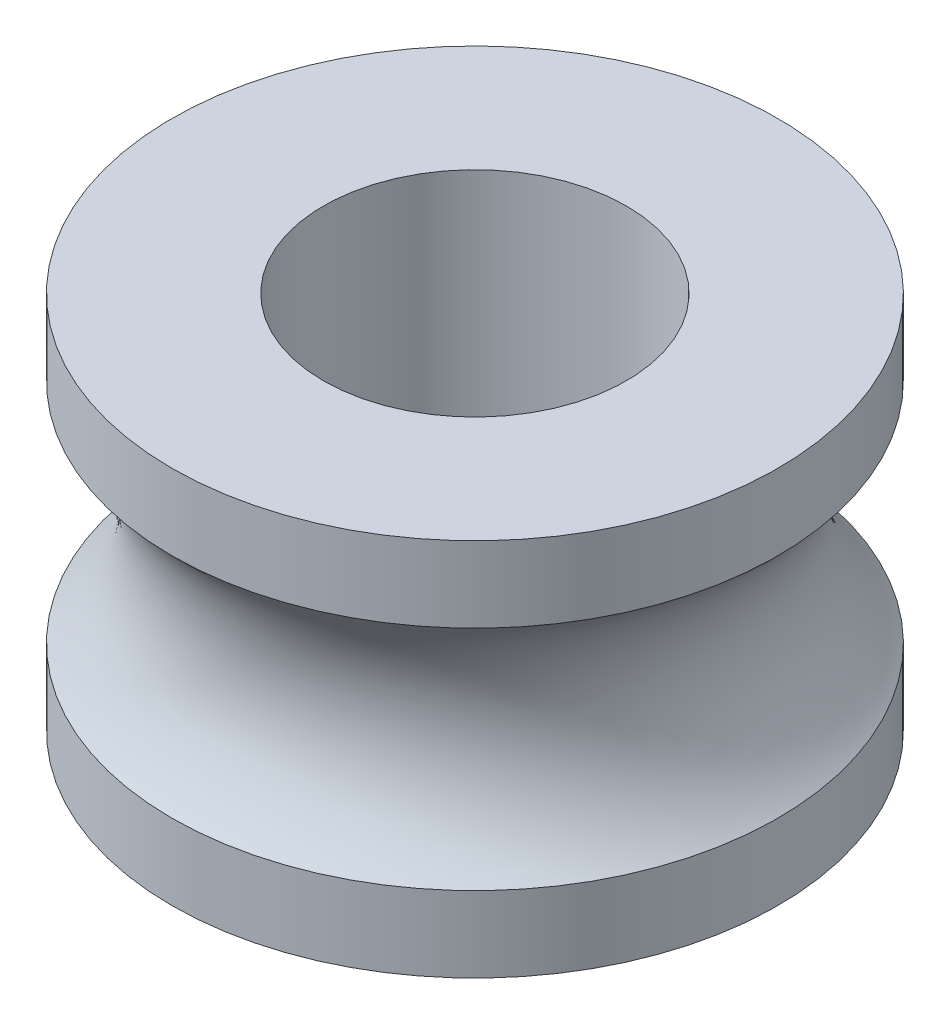
SolidWorks part; units mm, degrees
ref_plane "前视基准面" through (0, 0, 0) normal (0, 0, 1) x (1, 0, 0)
ref_plane "上视基准面" through (0, 0, 0) normal (0, 1, 0) x (1, 0, 0)
ref_plane "右视基准面" through (0, 0, 0) normal (1, 0, 0) x (0, 0, -1)
sketch "草图1" plane through (0, 0, 0) normal (0, 0, 1) x (1, 0, 0)
  line L0 (0, 2) -> (0, -2) construction
  line L1 (2, -2.5) -> (2, 2.5)
  line L2 (2, 2.5) -> (4, 2.5)
  line L3 (4, 2.5) -> (4, 1.5)
  line L4 (2, -2.5) -> (4, -2.5)
  line L5 (4, -2.5) -> (4, -1.5)
  line L6 (0, 0) -> (5.3229, 0) construction
  arc A0 (4, 1.5) -> (4, -1.5) centre (5.3229, 0) ccw
  point P4 (0, 0)
  dimension "D1" = 4
  dimension "D5" = 2
  dimension "D2" = 4
  dimension "D3" = 8
  dimension "D4" = 8
  dimension "D6" = 1
  dimension "D7" = 5
  dimension "D8" = 1
revolve "旋转1" add sketch "草图1" angle 360 about L0
